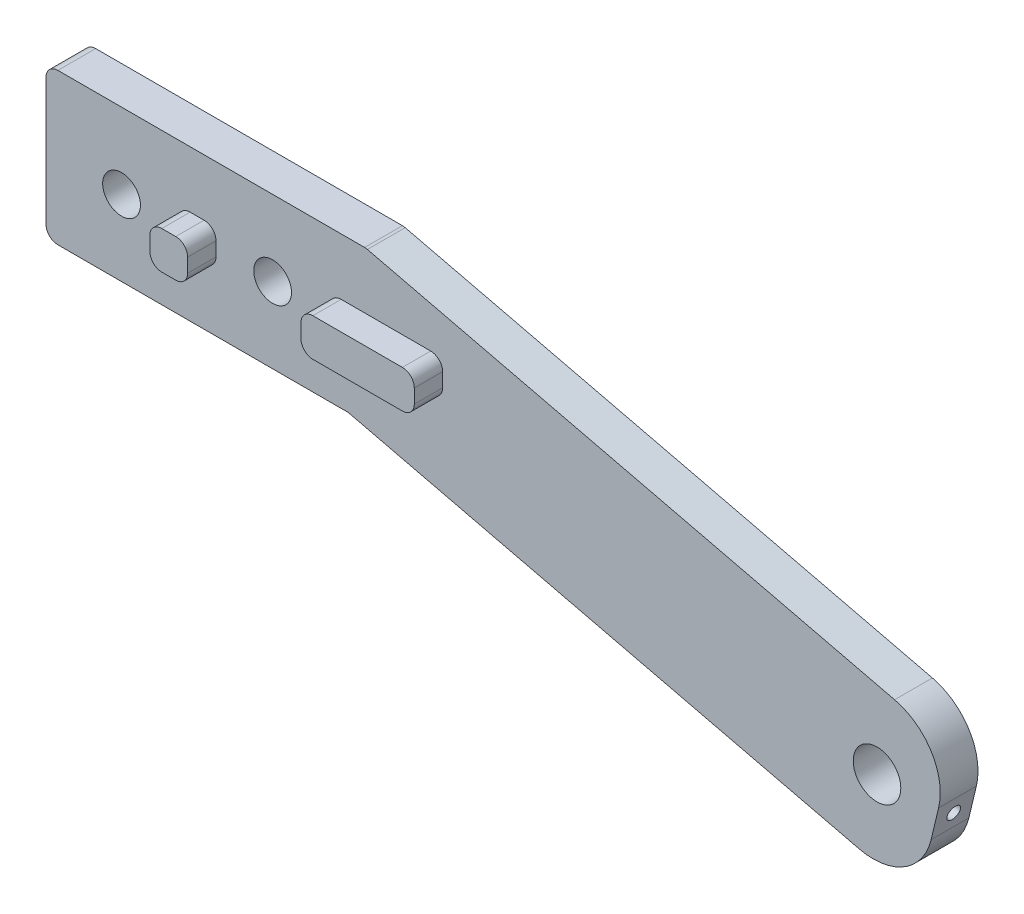
SolidWorks part; units mm, degrees
ref_plane "Front Plane" through (0, 0, 0) normal (0, 0, 1) x (1, 0, 0)
ref_plane "Top Plane" through (0, 0, 0) normal (0, 1, 0) x (1, 0, 0)
ref_plane "Right Plane" through (0, 0, 0) normal (1, 0, 0) x (0, 0, -1)
sketch "Sketch1" plane through (0, 0, 0) normal (0, 0, 1) x (1, 0, 0)
  line L0 (-25.4, 0) -> (-38.1, 0) construction
  line L2 (-38.1, -12.7) -> (-38.1, 12.7)
  line L5 (104.5604, -8.5999) -> (98.6396, -33.3001) construction
  line L6 (12.7, -12.7) -> (71.3084, -26.7487) construction
  line L19 (-25.4, 0) -> (0, 0) construction
  line L25 (15.7017, 12.7) -> (-38.1, 12.7)
  line L26 (12.7, -12.7) -> (-38.1, -12.7)
  line L27 (15.7017, 12.7) -> (74.6646, -1.4337) construction
  line L28 (15.7017, 12.7) -> (114.2849, -10.9309)
  line L29 (12.7, -12.7) -> (108.3641, -35.6312)
  line L30 (108.3641, -35.6312) -> (114.2849, -10.9309)
  circle A0 centre (-25.4, 0) radius 3.175
  circle A12 centre (0, 0) radius 3.175
  circle A13 centre (101.6, -20.95) radius 4
  point P8 (0, 0)
  point P16 (64.2348, -43.9487)
  point P17 (0, 0)
  dimension "D4" = 6.35
  dimension "D7" = 10
  dimension "D8" = 25.4
  dimension "D5" = 101.6
  dimension "D6" = 20.95
  dimension "D9" = 8
  dimension "D2" = 50.8
  dimension "D3" = 12.7
  dimension "D12" = 25.4
  dimension "D13" = 25.4
extrude "Boss-Extrude1" add sketch "Sketch1" along normal blind 6.35
sketch "Sketch3" plane through (110.5529, -26.5001, 0) normal (0.9725, -0.2331, 0) x (0, 0, -1)
  line L0 (-6.35, 3.3102) -> (0, 3.3102) construction
  line L1 (-6.35, -9.3898) -> (-6.35, 16.0102) construction
  line L2 (0, -9.3898) -> (0, 16.0102) construction
  circle A0 centre (-3.175, 3.3102) radius 1.1303
  dimension "D1" = 2.2606
extrude "Cut-Extrude2" cut sketch "Sketch3" against normal up to next
fillet "Fillet4" radius 10 2 edges at (108.3641, -35.6312, 3.175) (114.2849, -10.9309, 3.175)
sketch "Sketch4" plane through (0, 0, 6.35) normal (0, 0, 1) x (1, 0, 0)
  line L0 (-15.875, -3.175) -> (-15.875, 3.175)
  line L1 (-15.875, -3.175) -> (-9.525, -3.175)
  line L2 (-15.875, 3.175) -> (-9.525, 3.175)
  line L3 (-9.525, -3.175) -> (-9.525, 3.175)
  line L4 (-15.875, -3.175) -> (-9.525, 3.175) construction
  line L5 (-15.875, 3.175) -> (-9.525, -3.175) construction
  line L6 (-25.4, 0) -> (0, 0) construction
  line L7 (0, 0) -> (24.101, 0) construction
  line L8 (9.525, -3.175) -> (9.525, 3.175)
  line L9 (9.525, -3.175) -> (28.575, -3.175)
  line L10 (9.525, 3.175) -> (28.575, 3.175)
  line L11 (28.575, -3.175) -> (28.575, 3.175)
  line L12 (9.525, -3.175) -> (28.575, 3.175) construction
  line L13 (9.525, 3.175) -> (28.575, -3.175) construction
  circle A1 centre (-25.4, 0) radius 3.175 construction
  point P1 (-12.7, 0)
  point P11 (0, 0)
  point P14 (19.05, 0)
  dimension "D2" = 9.525
  dimension "D1" = 6.35
  dimension "D3" = 9.525
  dimension "D4" = 19.05
extrude "Boss-Extrude2" add sketch "Sketch4" along normal blind 4.7625
fillet "Fillet3" radius 2 12 edges at (-38.1, -12.7, 3.175) (-38.1, 12.7, 3.175) (12.7, -12.7, 3.175) (15.7017, 12.7, 3.175) (28.575, -3.175, 8.7312) (28.575, 3.175, 8.7312) (9.525, 3.175, 8.7312) (9.525, -3.175, 8.7312) (-9.525, 3.175, 8.7312) (-9.525, -3.175, 8.7312) (-15.875, -3.175, 8.7312) (-15.875, 3.175, 8.7312)
